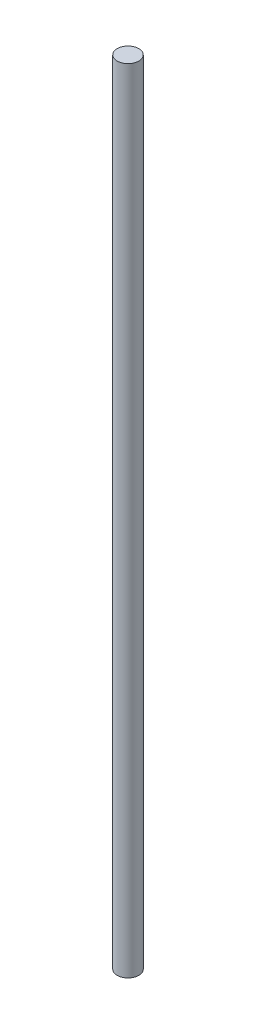
SolidWorks part; units mm, degrees
ref_plane "前视基准面" through (0, 0, 0) normal (0, 0, 1) x (1, 0, 0)
ref_plane "上视基准面" through (0, 0, 0) normal (0, 1, 0) x (1, 0, 0)
ref_plane "右视基准面" through (0, 0, 0) normal (1, 0, 0) x (0, 0, -1)
sketch "草图1" plane through (0, 0, 0) normal (0, 1, 0) x (1, 0, 0)
  circle A0 centre (0, 0) radius 3
  dimension "D1" = 6
extrude "凸台-拉伸1" add sketch "草图1" along normal blind 220
